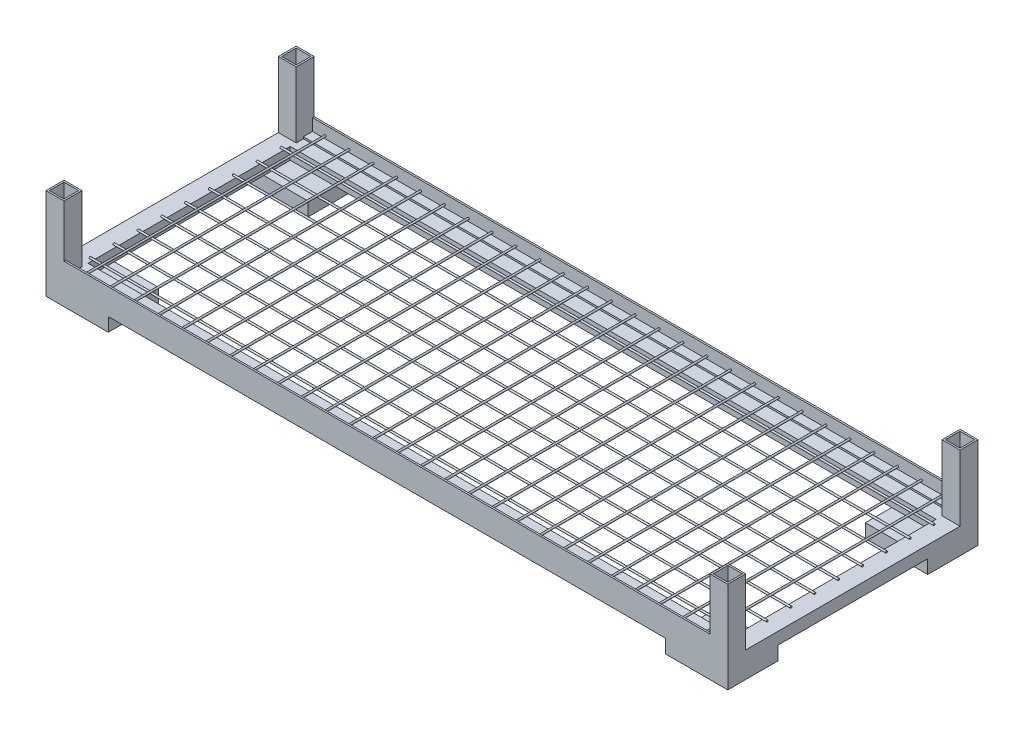
SolidWorks part; units mm, degrees
ref_plane "Front Plane" through (0, 0, 0) normal (0, 0, 1) x (1, 0, 0)
ref_plane "Top Plane" through (0, 0, 0) normal (0, 1, 0) x (1, 0, 0)
ref_plane "Right Plane" through (0, 0, 0) normal (1, 0, 0) x (0, 0, -1)
sketch "Sketch1" plane through (0, 0, 0) normal (0, 1, 0) x (1, 0, 0)
  line L1 (-722.3125, -265.1125) -> (722.3125, -265.1125)
  line L2 (-722.3125, -265.1125) -> (-722.3125, 265.1125)
  line L3 (-722.3125, 265.1125) -> (722.3125, 265.1125)
  line L4 (722.3125, -265.1125) -> (722.3125, 265.1125)
  line L5 (-722.3125, -265.1125) -> (722.3125, 265.1125) construction
  line L6 (-722.3125, 265.1125) -> (722.3125, -265.1125) construction
  line L7 (-684.2125, 214.3125) -> (684.2125, 214.3125)
  line L8 (-684.2125, 214.3125) -> (-684.2125, -214.3125)
  line L9 (-684.2125, -214.3125) -> (684.2125, -214.3125)
  line L10 (684.2125, 214.3125) -> (684.2125, -214.3125)
  line L11 (-684.2125, 214.3125) -> (684.2125, -214.3125) construction
  line L12 (-684.2125, -214.3125) -> (684.2125, 214.3125) construction
  point P0 (0, 0)
  dimension "D1" = 1444.625
  dimension "D2" = 530.225
  dimension "D4" = 38.1
  dimension "D5" = 50.8
  dimension "D3" = 38.1
  dimension "D6" = 50.8
extrude "Boss-Extrude1" add sketch "Sketch1" along normal blind 25.4
sketch "Sketch2" plane through (0, 25.4, 0) normal (0, 1, 0) x (1, 0, 0)
  line L0 (718.7565, -230.5685) -> (687.7685, -230.5685)
  line L1 (-722.3125, 265.1125) -> (-684.2125, 265.1125)
  line L2 (-722.3125, 265.1125) -> (-722.3125, 227.0125)
  line L3 (-722.3125, 227.0125) -> (-684.2125, 227.0125)
  line L4 (-684.2125, 265.1125) -> (-684.2125, 227.0125)
  line L5 (-722.3125, -265.1125) -> (-684.2125, -265.1125)
  line L6 (-722.3125, -265.1125) -> (-722.3125, -227.0125)
  line L7 (-722.3125, -227.0125) -> (-684.2125, -227.0125)
  line L8 (-684.2125, -265.1125) -> (-684.2125, -227.0125)
  line L9 (722.3125, -265.1125) -> (684.2125, -265.1125)
  line L10 (722.3125, -265.1125) -> (722.3125, -227.0125)
  line L11 (722.3125, -227.0125) -> (684.2125, -227.0125)
  line L12 (684.2125, -265.1125) -> (684.2125, -227.0125)
  line L13 (722.3125, 265.1125) -> (684.2125, 265.1125)
  line L14 (722.3125, 265.1125) -> (722.3125, 227.0125)
  line L15 (722.3125, 227.0125) -> (684.2125, 227.0125)
  line L16 (684.2125, 265.1125) -> (684.2125, 227.0125)
  line L17 (687.7685, -261.5565) -> (687.7685, -230.5685)
  line L18 (718.7565, -261.5565) -> (687.7685, -261.5565)
  line L19 (718.7565, -261.5565) -> (718.7565, -230.5685)
  line L20 (718.7565, 230.5685) -> (687.7685, 230.5685)
  line L21 (687.7685, 261.5565) -> (687.7685, 230.5685)
  line L22 (718.7565, 261.5565) -> (687.7685, 261.5565)
  line L23 (718.7565, 261.5565) -> (718.7565, 230.5685)
  line L24 (-687.7685, -261.5565) -> (-687.7685, -230.5685)
  line L25 (-718.7565, -230.5685) -> (-687.7685, -230.5685)
  line L26 (-718.7565, -261.5565) -> (-718.7565, -230.5685)
  line L27 (-718.7565, -261.5565) -> (-687.7685, -261.5565)
  line L28 (-687.7685, 261.5565) -> (-687.7685, 230.5685)
  line L29 (-718.7565, 230.5685) -> (-687.7685, 230.5685)
  line L30 (-718.7565, 261.5565) -> (-718.7565, 230.5685)
  line L31 (-718.7565, 261.5565) -> (-687.7685, 261.5565)
  dimension "D1" = 38.1
  dimension "D2" = 38.1
  dimension "D3" = 3.556
extrude "Boss-Extrude2" add sketch "Sketch2" along normal blind 139.7
sketch "Sketch3" plane through (0, 25.4, 0) normal (0, 1, 0) x (1, 0, 0)
  line L0 (684.2125, 265.1125) -> (684.2125, 227.0125) construction
  line L1 (-684.2125, 265.1125) -> (684.2125, 265.1125)
  line L2 (-684.2125, 265.1125) -> (-684.2125, 242.2525)
  line L3 (-684.2125, 242.2525) -> (684.2125, 242.2525)
  line L4 (684.2125, 265.1125) -> (684.2125, 242.2525)
  line L5 (684.2125, -227.0125) -> (684.2125, -265.1125) construction
  line L6 (-684.2125, -265.1125) -> (684.2125, -265.1125)
  line L7 (-684.2125, -265.1125) -> (-684.2125, -242.2525)
  line L8 (-684.2125, -242.2525) -> (684.2125, -242.2525)
  line L9 (684.2125, -265.1125) -> (684.2125, -242.2525)
  dimension "D1" = 22.86
extrude "Boss-Extrude3" add sketch "Sketch3" along normal blind 3.81
ref_plane "Plane1" through (-690.5625, 0, 0) normal (1, 0, 0) x (0, 0, -1)
sketch "Sketch4" plane through (-690.5625, 0, 0) normal (1, 0, 0) x (0, 0, -1)
  line L0 (227.0125, 25.4) -> (-227.0125, 25.4) construction
  circle A0 centre (-1.3181, 27.305) radius 1.905
  circle A1 centre (49.2279, 27.305) radius 1.905
  circle A2 centre (99.7739, 27.305) radius 1.905
  circle A3 centre (150.3199, 27.305) radius 1.905
  circle A4 centre (200.8659, 27.305) radius 1.905
  circle A5 centre (-51.8641, 27.305) radius 1.905
  circle A6 centre (-102.4101, 27.305) radius 1.905
  circle A7 centre (-152.9561, 27.305) radius 1.905
  circle A8 centre (-203.5021, 27.305) radius 1.905
  dimension "D1" = 1.905
  dimension "D2" = 3.81
  dimension "D3" = 5
  dimension "D4" = 5
extrude "Boss-Extrude4" add sketch "Sketch4" along normal blind 1384.3 separate body
sketch "Sketch5" plane through (0, 29.21, 0) normal (0, 1, 0) x (1, 0, 0)
  line L0 (-684.2125, -265.1125) -> (-684.2125, -227.0125) construction
  line L1 (684.2125, -265.1125) -> (-684.2125, -265.1125)
  line L2 (684.2125, -265.1125) -> (684.2125, -261.5565)
  line L3 (684.2125, -261.5565) -> (-684.2125, -261.5565)
  line L4 (-684.2125, -265.1125) -> (-684.2125, -261.5565)
  line L5 (-684.2125, 227.0125) -> (-684.2125, 265.1125) construction
  line L6 (684.2125, 265.1125) -> (-684.2125, 265.1125)
  line L7 (684.2125, 265.1125) -> (684.2125, 261.5565)
  line L8 (684.2125, 261.5565) -> (-684.2125, 261.5565)
  line L9 (-684.2125, 265.1125) -> (-684.2125, 261.5565)
  dimension "D1" = 3.556
extrude "Boss-Extrude5" add sketch "Sketch5" along normal blind 25.4
sketch "Sketch6" plane through (0, 0, 261.5565) normal (0, 0, -1) x (-1, 0, 0)
  line L0 (-684.2125, 29.21) -> (684.2125, 29.21) construction
  circle A0 centre (0, 34.925) radius 1.905
  circle A1 centre (50.546, 34.925) radius 1.905
  circle A2 centre (101.092, 34.925) radius 1.905
  circle A3 centre (151.638, 34.925) radius 1.905
  circle A4 centre (202.184, 34.925) radius 1.905
  circle A5 centre (252.73, 34.925) radius 1.905
  circle A6 centre (303.276, 34.925) radius 1.905
  circle A7 centre (353.822, 34.925) radius 1.905
  circle A8 centre (404.368, 34.925) radius 1.905
  circle A9 centre (454.914, 34.925) radius 1.905
  circle A10 centre (505.46, 34.925) radius 1.905
  circle A11 centre (556.006, 34.925) radius 1.905
  circle A12 centre (606.552, 34.925) radius 1.905
  circle A13 centre (657.098, 34.925) radius 1.905
  circle A14 centre (0, 34.925) radius 1.905
  circle A15 centre (50.546, 34.925) radius 1.905
  circle A16 centre (101.092, 34.925) radius 1.905
  circle A17 centre (151.638, 34.925) radius 1.905
  circle A18 centre (202.184, 34.925) radius 1.905
  circle A19 centre (252.73, 34.925) radius 1.905
  circle A20 centre (303.276, 34.925) radius 1.905
  circle A21 centre (353.822, 34.925) radius 1.905
  circle A22 centre (404.368, 34.925) radius 1.905
  circle A23 centre (454.914, 34.925) radius 1.905
  circle A24 centre (505.46, 34.925) radius 1.905
  circle A25 centre (556.006, 34.925) radius 1.905
  circle A26 centre (606.552, 34.925) radius 1.905
  circle A27 centre (-50.546, 34.925) radius 1.905
  circle A28 centre (0, 34.925) radius 1.905
  circle A29 centre (50.546, 34.925) radius 1.905
  circle A30 centre (101.092, 34.925) radius 1.905
  circle A31 centre (151.638, 34.925) radius 1.905
  circle A32 centre (202.184, 34.925) radius 1.905
  circle A33 centre (252.73, 34.925) radius 1.905
  circle A34 centre (303.276, 34.925) radius 1.905
  circle A35 centre (353.822, 34.925) radius 1.905
  circle A36 centre (404.368, 34.925) radius 1.905
  circle A37 centre (454.914, 34.925) radius 1.905
  circle A38 centre (505.46, 34.925) radius 1.905
  circle A39 centre (556.006, 34.925) radius 1.905
  circle A40 centre (-101.092, 34.925) radius 1.905
  circle A41 centre (-50.546, 34.925) radius 1.905
  circle A42 centre (0, 34.925) radius 1.905
  circle A43 centre (50.546, 34.925) radius 1.905
  circle A44 centre (101.092, 34.925) radius 1.905
  circle A45 centre (151.638, 34.925) radius 1.905
  circle A46 centre (202.184, 34.925) radius 1.905
  circle A47 centre (252.73, 34.925) radius 1.905
  circle A48 centre (303.276, 34.925) radius 1.905
  circle A49 centre (353.822, 34.925) radius 1.905
  circle A50 centre (404.368, 34.925) radius 1.905
  circle A51 centre (454.914, 34.925) radius 1.905
  circle A52 centre (505.46, 34.925) radius 1.905
  circle A53 centre (-151.638, 34.925) radius 1.905
  circle A54 centre (-101.092, 34.925) radius 1.905
  circle A55 centre (-50.546, 34.925) radius 1.905
  circle A56 centre (0, 34.925) radius 1.905
  circle A57 centre (50.546, 34.925) radius 1.905
  circle A58 centre (101.092, 34.925) radius 1.905
  circle A59 centre (151.638, 34.925) radius 1.905
  circle A60 centre (202.184, 34.925) radius 1.905
  circle A61 centre (252.73, 34.925) radius 1.905
  circle A62 centre (303.276, 34.925) radius 1.905
  circle A63 centre (353.822, 34.925) radius 1.905
  circle A64 centre (404.368, 34.925) radius 1.905
  circle A65 centre (454.914, 34.925) radius 1.905
  circle A66 centre (-202.184, 34.925) radius 1.905
  circle A67 centre (-151.638, 34.925) radius 1.905
  circle A68 centre (-101.092, 34.925) radius 1.905
  circle A69 centre (-50.546, 34.925) radius 1.905
  circle A70 centre (0, 34.925) radius 1.905
  circle A71 centre (50.546, 34.925) radius 1.905
  circle A72 centre (101.092, 34.925) radius 1.905
  circle A73 centre (151.638, 34.925) radius 1.905
  circle A74 centre (202.184, 34.925) radius 1.905
  circle A75 centre (252.73, 34.925) radius 1.905
  circle A76 centre (303.276, 34.925) radius 1.905
  circle A77 centre (353.822, 34.925) radius 1.905
  circle A78 centre (404.368, 34.925) radius 1.905
  circle A79 centre (-252.73, 34.925) radius 1.905
  circle A80 centre (-202.184, 34.925) radius 1.905
  circle A81 centre (-151.638, 34.925) radius 1.905
  circle A82 centre (-101.092, 34.925) radius 1.905
  circle A83 centre (-50.546, 34.925) radius 1.905
  circle A84 centre (0, 34.925) radius 1.905
  circle A85 centre (50.546, 34.925) radius 1.905
  circle A86 centre (101.092, 34.925) radius 1.905
  circle A87 centre (151.638, 34.925) radius 1.905
  circle A88 centre (202.184, 34.925) radius 1.905
  circle A89 centre (252.73, 34.925) radius 1.905
  circle A90 centre (303.276, 34.925) radius 1.905
  circle A91 centre (353.822, 34.925) radius 1.905
  circle A92 centre (-303.276, 34.925) radius 1.905
  circle A93 centre (-252.73, 34.925) radius 1.905
  circle A94 centre (-202.184, 34.925) radius 1.905
  circle A95 centre (-151.638, 34.925) radius 1.905
  circle A96 centre (-101.092, 34.925) radius 1.905
  circle A97 centre (-50.546, 34.925) radius 1.905
  circle A98 centre (0, 34.925) radius 1.905
  circle A99 centre (50.546, 34.925) radius 1.905
  circle A100 centre (101.092, 34.925) radius 1.905
  circle A101 centre (151.638, 34.925) radius 1.905
  circle A102 centre (202.184, 34.925) radius 1.905
  circle A103 centre (252.73, 34.925) radius 1.905
  circle A104 centre (303.276, 34.925) radius 1.905
  circle A105 centre (-353.822, 34.925) radius 1.905
  circle A106 centre (-303.276, 34.925) radius 1.905
  circle A107 centre (-252.73, 34.925) radius 1.905
  circle A108 centre (-202.184, 34.925) radius 1.905
  circle A109 centre (-151.638, 34.925) radius 1.905
  circle A110 centre (-101.092, 34.925) radius 1.905
  circle A111 centre (-50.546, 34.925) radius 1.905
  circle A112 centre (0, 34.925) radius 1.905
  circle A113 centre (50.546, 34.925) radius 1.905
  circle A114 centre (101.092, 34.925) radius 1.905
  circle A115 centre (151.638, 34.925) radius 1.905
  circle A116 centre (202.184, 34.925) radius 1.905
  circle A117 centre (252.73, 34.925) radius 1.905
  circle A118 centre (-404.368, 34.925) radius 1.905
  circle A119 centre (-353.822, 34.925) radius 1.905
  circle A120 centre (-303.276, 34.925) radius 1.905
  circle A121 centre (-252.73, 34.925) radius 1.905
  circle A122 centre (-202.184, 34.925) radius 1.905
  circle A123 centre (-151.638, 34.925) radius 1.905
  circle A124 centre (-101.092, 34.925) radius 1.905
  circle A125 centre (-50.546, 34.925) radius 1.905
  circle A126 centre (0, 34.925) radius 1.905
  circle A127 centre (50.546, 34.925) radius 1.905
  circle A128 centre (101.092, 34.925) radius 1.905
  circle A129 centre (151.638, 34.925) radius 1.905
  circle A130 centre (202.184, 34.925) radius 1.905
  circle A131 centre (-454.914, 34.925) radius 1.905
  circle A132 centre (-404.368, 34.925) radius 1.905
  circle A133 centre (-353.822, 34.925) radius 1.905
  circle A134 centre (-303.276, 34.925) radius 1.905
  circle A135 centre (-252.73, 34.925) radius 1.905
  circle A136 centre (-202.184, 34.925) radius 1.905
  circle A137 centre (-151.638, 34.925) radius 1.905
  circle A138 centre (-101.092, 34.925) radius 1.905
  circle A139 centre (-50.546, 34.925) radius 1.905
  circle A140 centre (0, 34.925) radius 1.905
  circle A141 centre (50.546, 34.925) radius 1.905
  circle A142 centre (101.092, 34.925) radius 1.905
  circle A143 centre (151.638, 34.925) radius 1.905
  circle A144 centre (-505.46, 34.925) radius 1.905
  circle A145 centre (-454.914, 34.925) radius 1.905
  circle A146 centre (-404.368, 34.925) radius 1.905
  circle A147 centre (-353.822, 34.925) radius 1.905
  circle A148 centre (-303.276, 34.925) radius 1.905
  circle A149 centre (-252.73, 34.925) radius 1.905
  circle A150 centre (-202.184, 34.925) radius 1.905
  circle A151 centre (-151.638, 34.925) radius 1.905
  circle A152 centre (-101.092, 34.925) radius 1.905
  circle A153 centre (-50.546, 34.925) radius 1.905
  circle A154 centre (0, 34.925) radius 1.905
  circle A155 centre (50.546, 34.925) radius 1.905
  circle A156 centre (101.092, 34.925) radius 1.905
  circle A157 centre (-556.006, 34.925) radius 1.905
  circle A158 centre (-505.46, 34.925) radius 1.905
  circle A159 centre (-454.914, 34.925) radius 1.905
  circle A160 centre (-404.368, 34.925) radius 1.905
  circle A161 centre (-353.822, 34.925) radius 1.905
  circle A162 centre (-303.276, 34.925) radius 1.905
  circle A163 centre (-252.73, 34.925) radius 1.905
  circle A164 centre (-202.184, 34.925) radius 1.905
  circle A165 centre (-151.638, 34.925) radius 1.905
  circle A166 centre (-101.092, 34.925) radius 1.905
  circle A167 centre (-50.546, 34.925) radius 1.905
  circle A168 centre (0, 34.925) radius 1.905
  circle A169 centre (50.546, 34.925) radius 1.905
  circle A170 centre (-606.552, 34.925) radius 1.905
  circle A171 centre (-556.006, 34.925) radius 1.905
  circle A172 centre (-505.46, 34.925) radius 1.905
  circle A173 centre (-454.914, 34.925) radius 1.905
  circle A174 centre (-404.368, 34.925) radius 1.905
  circle A175 centre (-353.822, 34.925) radius 1.905
  circle A176 centre (-303.276, 34.925) radius 1.905
  circle A177 centre (-252.73, 34.925) radius 1.905
  circle A178 centre (-202.184, 34.925) radius 1.905
  circle A179 centre (-151.638, 34.925) radius 1.905
  circle A180 centre (-101.092, 34.925) radius 1.905
  circle A181 centre (-50.546, 34.925) radius 1.905
  circle A182 centre (0, 34.925) radius 1.905
  circle A183 centre (-50.546, 34.925) radius 1.905
  circle A184 centre (-101.092, 34.925) radius 1.905
  circle A185 centre (-151.638, 34.925) radius 1.905
  circle A186 centre (-202.184, 34.925) radius 1.905
  circle A187 centre (-252.73, 34.925) radius 1.905
  circle A188 centre (-303.276, 34.925) radius 1.905
  circle A189 centre (-353.822, 34.925) radius 1.905
  circle A190 centre (-404.368, 34.925) radius 1.905
  circle A191 centre (-454.914, 34.925) radius 1.905
  circle A192 centre (-505.46, 34.925) radius 1.905
  circle A193 centre (-556.006, 34.925) radius 1.905
  circle A194 centre (-606.552, 34.925) radius 1.905
  circle A195 centre (-657.098, 34.925) radius 1.905
  dimension "D1" = 3.81
  dimension "D2" = 5.715
  dimension "D3" = 14
  dimension "D4" = 14
extrude "Boss-Extrude6" add sketch "Sketch6" along normal blind 523.113
sketch "Sketch7" plane through (0, 0, 0) normal (0, -1, 0) x (1, 0, 0)
  line L1 (-722.3125, -265.1125) -> (-590.2325, -265.1125)
  line L2 (-722.3125, -265.1125) -> (-722.3125, -158.4325)
  line L3 (-722.3125, -158.4325) -> (-590.2325, -158.4325)
  line L4 (-590.2325, -265.1125) -> (-590.2325, -158.4325)
  line L5 (-722.3125, 265.1125) -> (-590.2325, 265.1125)
  line L6 (-722.3125, 265.1125) -> (-722.3125, 158.4325)
  line L7 (-722.3125, 158.4325) -> (-590.2325, 158.4325)
  line L8 (-590.2325, 265.1125) -> (-590.2325, 158.4325)
  line L9 (722.3125, -265.1125) -> (590.2325, -265.1125)
  line L10 (722.3125, -265.1125) -> (722.3125, -158.4325)
  line L11 (722.3125, -158.4325) -> (590.2325, -158.4325)
  line L12 (590.2325, -265.1125) -> (590.2325, -158.4325)
  line L13 (722.3125, 265.1125) -> (590.2325, 265.1125)
  line L14 (722.3125, 265.1125) -> (722.3125, 158.4325)
  line L15 (722.3125, 158.4325) -> (590.2325, 158.4325)
  line L16 (590.2325, 265.1125) -> (590.2325, 158.4325)
  dimension "D1" = 132.08
  dimension "D2" = 106.68
extrude "Boss-Extrude7" add sketch "Sketch7" along normal blind 3.556
sketch "Sketch8" plane through (0, -3.556, 0) normal (0, -1, 0) x (1, 0, 0)
  line L0 (-718.7565, -261.5565) -> (-593.7885, -261.5565)
  line L1 (-722.3125, -265.1125) -> (-590.2325, -265.1125)
  line L2 (-722.3125, -265.1125) -> (-722.3125, -158.4325)
  line L3 (-722.3125, -158.4325) -> (-590.2325, -158.4325)
  line L4 (-590.2325, -265.1125) -> (-590.2325, -158.4325)
  line L5 (-722.3125, 265.1125) -> (-590.2325, 265.1125)
  line L6 (-722.3125, 265.1125) -> (-722.3125, 158.4325)
  line L7 (-722.3125, 158.4325) -> (-590.2325, 158.4325)
  line L8 (-590.2325, 265.1125) -> (-590.2325, 158.4325)
  line L9 (590.2325, 158.4325) -> (722.3125, 158.4325)
  line L10 (590.2325, 158.4325) -> (590.2325, 265.1125)
  line L11 (590.2325, 265.1125) -> (722.3125, 265.1125)
  line L12 (722.3125, 158.4325) -> (722.3125, 265.1125)
  line L13 (590.2325, -158.4325) -> (722.3125, -158.4325)
  line L14 (590.2325, -158.4325) -> (590.2325, -265.1125)
  line L15 (590.2325, -265.1125) -> (722.3125, -265.1125)
  line L16 (722.3125, -158.4325) -> (722.3125, -265.1125)
  line L17 (-593.7885, -261.5565) -> (-593.7885, -161.9885)
  line L18 (-718.7565, -161.9885) -> (-593.7885, -161.9885)
  line L19 (-718.7565, -261.5565) -> (-718.7565, -161.9885)
  line L20 (-718.7565, 261.5565) -> (-593.7885, 261.5565)
  line L21 (-593.7885, 261.5565) -> (-593.7885, 161.9885)
  line L22 (-718.7565, 161.9885) -> (-593.7885, 161.9885)
  line L23 (-718.7565, 261.5565) -> (-718.7565, 161.9885)
  line L24 (593.7885, 161.9885) -> (718.7565, 161.9885)
  line L25 (718.7565, 161.9885) -> (718.7565, 261.5565)
  line L26 (593.7885, 261.5565) -> (718.7565, 261.5565)
  line L27 (593.7885, 161.9885) -> (593.7885, 261.5565)
  line L28 (593.7885, -161.9885) -> (718.7565, -161.9885)
  line L29 (718.7565, -161.9885) -> (718.7565, -261.5565)
  line L30 (593.7885, -261.5565) -> (718.7565, -261.5565)
  line L31 (593.7885, -161.9885) -> (593.7885, -261.5565)
  dimension "D1" = 3.556
extrude "Boss-Extrude8" add sketch "Sketch8" along normal blind 25.4
